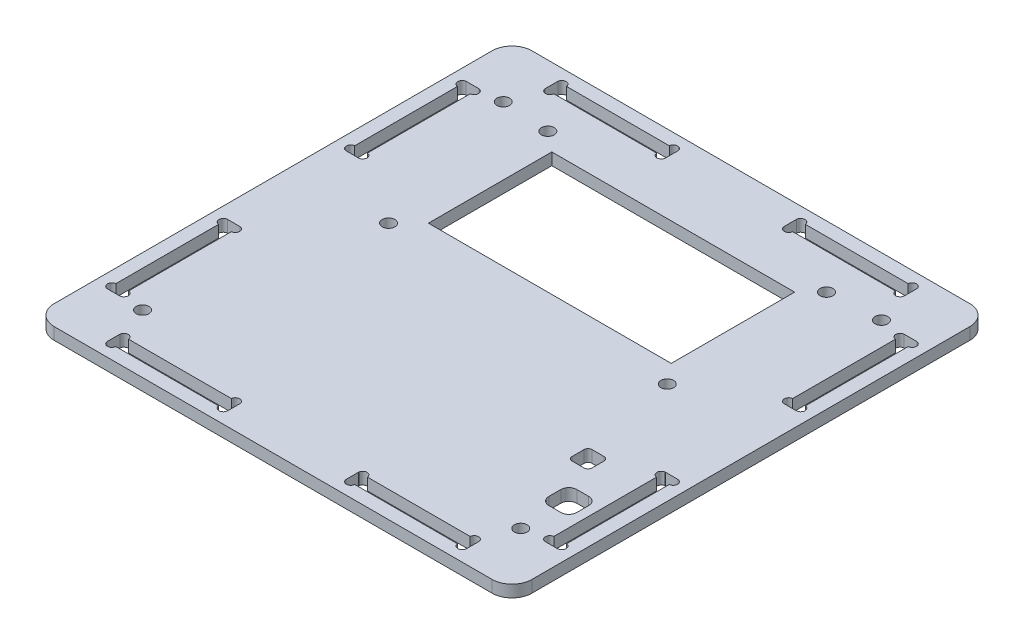
SolidWorks part; units mm, degrees
material "轻木"
ref_plane "Front" through (0, 0, 0) normal (0, 0, 1) x (1, 0, 0)
ref_plane "Top" through (0, 0, 0) normal (0, 1, 0) x (1, 0, 0)
ref_plane "Right" through (0, 0, 0) normal (1, 0, 0) x (0, 0, -1)
sketch "草图1" plane through (0, 0, 0) normal (0, 1, 0) x (1, 0, 0)
  line L1 (-60, 60) -> (60, 60)
  line L2 (-60, 60) -> (-60, -60)
  line L3 (-60, -60) -> (60, -60)
  line L4 (60, 60) -> (60, -60)
  line L5 (0, -60) -> (0, 60) construction
  line L6 (-60, 0) -> (60, 0) construction
  line L7 (-47.5, -45.3) -> (47.5, -45.3) construction
  line L8 (-47.5, -45.3) -> (-47.5, 45.3) construction
  line L9 (-47.5, 45.3) -> (47.5, 45.3) construction
  line L10 (47.5, -45.3) -> (47.5, 45.3) construction
  line L11 (0, 45.3) -> (0, -45.3) construction
  line L12 (-47.5, 0) -> (47.5, 0) construction
  circle A0 centre (-47.5, 45.3) radius 1.6
  circle A1 centre (47.5, 45.3) radius 1.6
  circle A2 centre (47.5, -45.3) radius 1.6
  circle A3 centre (-47.5, -45.3) radius 1.6
  point P0 (0, 0)
  point P4 (0, 0)
  point P95 (0.9739, 0)
  dimension "D7" = 3.2
  dimension "D1" = 120
  dimension "D2" = 120
  dimension "D3" = 95
  dimension "D4" = 90.6
extrude "凸台-拉伸1" add sketch "草图1" along normal blind 3
sketch "草图2" plane through (0, 3, 0) normal (0, 1, 0) x (1, 0, 0)
  line L0 (-60, 55) -> (60, 55) construction
  line L1 (-60, 60) -> (-60, -60) construction
  line L2 (60, -60) -> (60, 60) construction
  line L3 (-60, -55) -> (60, -55) construction
  line L4 (-45.1, 53.4) -> (-14.9, 53.4)
  line L5 (0, 55) -> (0, -55) construction
  line L6 (-14.9, 53.4) -> (-14.9, 56.6)
  line L7 (-45, 53.5) -> (-15, 53.5)
  line L8 (-45, 53.5) -> (-45, 56.5)
  line L9 (-45, 56.5) -> (-15, 56.5)
  line L10 (-15, 53.5) -> (-15, 56.5)
  line L11 (-30, 56.5) -> (-30, 53.5) construction
  line L12 (-45, 55) -> (-15, 55) construction
  line L13 (-45.1, 56.6) -> (-14.9, 56.6)
  line L14 (-45.1, 53.4) -> (-45.1, 56.6)
  line L15 (-30.1, 56.5) -> (-30.1, 53.5)
  line L16 (-45, 54.9) -> (-15, 54.9)
  circle A0 centre (-16.0003, 56.5) radius 1.0003
  circle A1 centre (-16.0003, 53.5) radius 1.0003
  circle A2 centre (-43.9997, 56.5) radius 1.0003
  circle A3 centre (-43.9997, 53.5) radius 1.0003
  circle A4 centre (-16.0003, 56.5) radius 1.1003
  circle A5 centre (-16.0003, 53.5) radius 1.1003
  circle A6 centre (-43.9997, 56.5) radius 1.1003
  circle A7 centre (-43.9997, 53.5) radius 1.1003
  point P10 (0, 0)
  point P11 (-30, 55)
  dimension "D5" = 2.0006
  dimension "D1" = 110
  dimension "D2" = 30
  dimension "D3" = 30
  dimension "D4" = 3
  dimension "D6" = 0.1
extrude "切除-拉伸1" cut sketch "草图2" against normal blind 10 contours A6 | A7 | L13 L6 L4 L14 | A4 | A5
mirror "镜向1" about plane through (0, 0, 0) normal (1, 0, 0) of "切除-拉伸1"
sketch "草图3" plane through (0, 0, 0) normal (1, 0, 0) x (0, 0, -1)
  line L0 (0, 0) -> (0, 42.0396) construction
pattern_circular "阵列(圆周)1" count 4 over 360 about axis through (0, 0, 0) along (0, 1, 0) of "镜向1", "切除-拉伸1"
fillet "圆角1" radius 5 4 edges at (60, 1.5, 60) (-60, 1.5, 60) (60, 1.5, -60) (-60, 1.5, -60)
sketch "草图5" plane through (0, 0, 0) normal (0, -1, 0) x (1, 0, 0)
  line L1 (44.071, 29.8) -> (51.071, 29.8)
  line L2 (44.071, 29.8) -> (44.071, 36.8)
  line L3 (44.071, 36.8) -> (51.071, 36.8)
  line L4 (51.071, 29.8) -> (51.071, 36.8)
  line L5 (47.571, 36.8) -> (47.571, 29.8) construction
  line L6 (44.071, 33.3) -> (51.071, 33.3) construction
  circle A0 centre (47.5, 45.3) radius 1.6 construction
  point P0 (47.571, 33.3)
  dimension "D1" = 12
  dimension "D2" = 7
  dimension "D3" = 7
extrude "切除-拉伸3" cut sketch "草图5" against normal blind 10
fillet "圆角2" radius 2 4 edges at (51.071, 1.5, 29.8) (44.071, 1.5, 29.8) (51.071, 1.5, 36.8) (44.071, 1.5, 36.8)
sketch "草图6" plane through (0, 0, 0) normal (0, -1, 0) x (1, 0, 0)
  line L4 (38.3, 19.2) -> (43.3, 19.2)
  line L5 (43.3, 19.2) -> (43.3, 24.2)
  line L6 (43.3, 24.2) -> (38.3, 24.2)
  line L7 (38.3, 24.2) -> (38.3, 19.2)
  line L8 (38.3, 19.2) -> (43.3, 19.2)
  line L9 (43.3, 19.2) -> (43.3, 24.2)
  line L10 (43.3, 24.2) -> (38.3, 24.2)
  line L11 (38.3, 24.2) -> (38.3, 19.2)
  dimension "D1" = 0
extrude "切除-拉伸4" cut sketch "草图6" against normal blind 5
fillet "圆角3" radius 1 4 edges at (43.3, 1.5, 24.2) (43.3, 1.5, 19.2) (38.3, 1.5, 19.2) (38.3, 1.5, 24.2)
sketch "草图7" plane through (0, 0, 0) normal (0, -1, 0) x (1, 0, 0)
  line L0 (0, -7) -> (54.2025, -7) construction
  line L1 (55, -60) -> (-55, -60) construction
  line L3 (-30.5, -40.5) -> (30.5, -40.5)
  line L4 (-30.5, -40.5) -> (-30.5, -9.5)
  line L5 (-30.5, -9.5) -> (30.5, -9.5)
  line L6 (30.5, -40.5) -> (30.5, -9.5)
  line L7 (0, -9.5) -> (0, -40.5) construction
  line L8 (-30.5, -25) -> (30.5, -25) construction
  point P4 (0, -25)
  dimension "D1" = 53
  dimension "D2" = 61
  dimension "D3" = 31
  dimension "D4" = 18
extrude "切除-拉伸5" cut sketch "草图7" against normal blind 10
sketch "草图8" plane through (0, 0, 0) normal (0, -1, 0) x (1, 0, 0)
  circle A1 centre (-35.5, -44.5) radius 1.6
  circle A2 centre (-35.5, -44.5) radius 1.6
  circle A3 centre (34.5, -44.5) radius 1.6
  circle A4 centre (34.5, -44.5) radius 1.6
  circle A5 centre (34.5, -4.5) radius 1.6
  circle A6 centre (34.5, -4.5) radius 1.6
  circle A7 centre (-35.5, -4.5) radius 1.6
  circle A8 centre (-35.5, -4.5) radius 1.6
  dimension "D1" = 0
  dimension "D2" = 0
  dimension "D3" = 0
  dimension "D4" = 0
extrude "切除-拉伸6" cut sketch "草图8" against normal blind 10
equation "\"8、\"=10"
